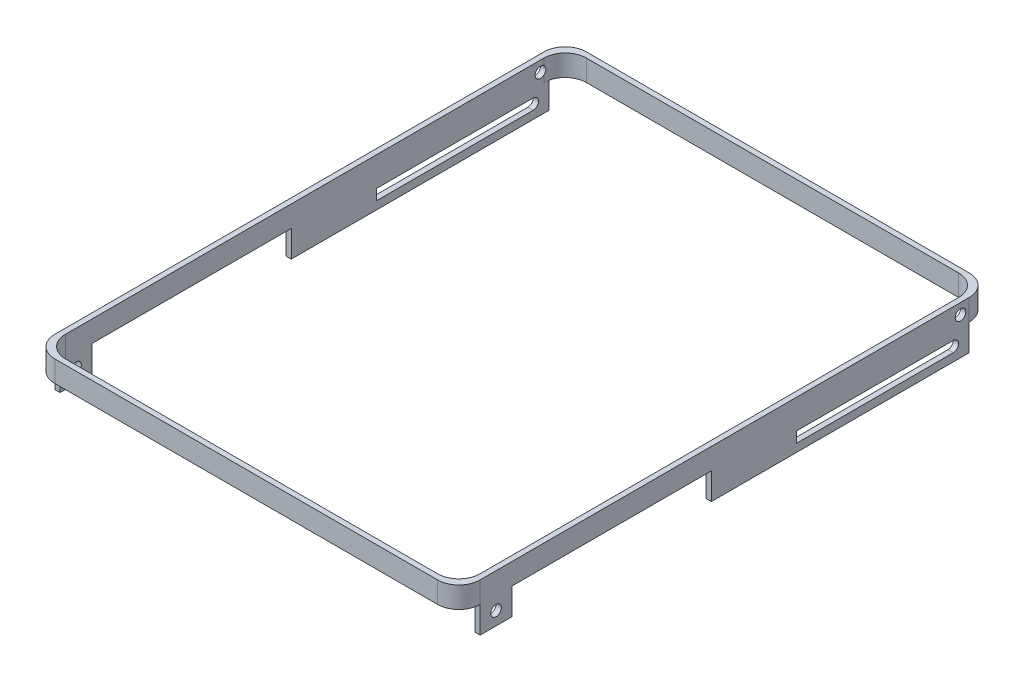
SolidWorks part; units mm, degrees
ref_plane "Front Plane" through (0, 0, 0) normal (0, 0, 1) x (1, 0, 0)
ref_plane "Top Plane" through (0, 0, 0) normal (0, 1, 0) x (1, 0, 0)
ref_plane "Right Plane" through (0, 0, 0) normal (1, 0, 0) x (0, 0, -1)
sketch "Sketch5" plane through (0, 0, 0) normal (0, 1, 0) x (1, 0, 0)
  line L1 (-180, 250) -> (180, 250)
  line L2 (-200, 230) -> (-200, -230)
  line L3 (-180, -250) -> (180, -250)
  line L4 (200, 230) -> (200, -230)
  line L5 (-200, 250) -> (200, -250) construction
  line L6 (-200, -250) -> (200, 250) construction
  arc A0 (-200, -230) -> (-180, -250) centre (-180, -230) ccw
  arc A1 (180, -250) -> (200, -230) centre (180, -230) ccw
  arc A2 (180, 250) -> (200, 230) centre (180, 230) cw
  arc A3 (-180, 250) -> (-200, 230) centre (-180, 230) ccw
  point P0 (0, 0)
  dimension "D3" = 20
  dimension "D1" = 500
  dimension "D2" = 400
extrude "Boss-Extrude2" add sketch "Sketch5" along normal blind 20
sketch "Sketch6" plane through (0, 20, 0) normal (0, 1, 0) x (1, 0, 0)
  line L1 (-175, -245) -> (175, -245)
  line L2 (-195, -225) -> (-195, 225)
  line L3 (-175, 245) -> (175, 245)
  line L4 (195, -225) -> (195, 225)
  line L5 (-195, -245) -> (195, 245) construction
  line L6 (-195, 245) -> (195, -245) construction
  arc A0 (-175, -245) -> (-195, -225) centre (-175, -225) cw
  arc A1 (175, -245) -> (195, -225) centre (175, -225) ccw
  arc A2 (175, 245) -> (195, 225) centre (175, 225) cw
  arc A3 (-195, 225) -> (-175, 245) centre (-175, 225) cw
  point P0 (0, 0)
  dimension "D3" = 20
  dimension "D1" = 490
  dimension "D2" = 390
extrude "Cut-Extrude1" cut sketch "Sketch6" against normal blind 20
sketch "Sketch7" plane through (200, 0, 0) normal (1, 0, 0) x (0, 0, -1)
  line L0 (230, 0) -> (230, -25)
  line L1 (230, -25) -> (-12.5565, -25)
  line L2 (-12.5565, -25) -> (-12.5565, 0)
  line L3 (-230, 0) -> (230, 0) construction
  line L4 (-12.5565, 0) -> (230, 0)
  dimension "D1" = 25
extrude "Boss-Extrude3" add sketch "Sketch7" against normal blind 5
sketch "Sketch8" plane through (-200, 0, 0) normal (-1, 0, 0) x (0, 0, 1)
  line L0 (-230, -25) -> (-230, 0) construction
  line L1 (12.5565, 0) -> (12.5565, -25) construction
  line L2 (12.5565, -25) -> (-230, -25) construction
  line L3 (-230, -25) -> (-230, 0)
  line L4 (12.5565, 0) -> (12.5565, -25)
  line L5 (12.5565, -25) -> (-230, -25)
  line L6 (-230, 0) -> (12.5565, 0)
extrude "Boss-Extrude4" add sketch "Sketch8" against normal blind 5
sketch "Sketch9" plane through (-200, 0, 0) normal (-1, 0, 0) x (0, 0, 1)
  line L0 (12.5565, 0) -> (-230, 0) construction
sketch "Sketch10" plane through (200, 0, 0) normal (1, 0, 0) x (0, 0, -1)
  line L10 (214.9751, -7.5) -> (2.4435, -7.5)
  line L13 (-12.5565, 0) -> (230, 0) construction
  line L15 (230, -25) -> (230, 0) construction
  line L16 (-12.5565, 0) -> (-12.5565, -25) construction
  line L18 (217.347, -16.9016) -> (215, -16.9016) construction
  line L20 (2.4435, -17.5) -> (214.9751, -17.5)
  arc A1 (2.4435, -7.5) -> (2.4435, -17.5) centre (2.4435, -12.5) ccw
  arc A3 (214.9751, -17.5) -> (214.9751, -7.5) centre (214.9751, -12.5) ccw
  dimension "D11" = 10
  dimension "D12" = 15.0249
  dimension "D14" = 5
  dimension "D13" = 15
  dimension "D15" = 212.5317
  dimension "D16" = 212.5317
extrude "Cut-Extrude2" cut sketch "Sketch10" against normal through all both and the other way through all
sketch "Sketch11" plane through (200, 0, 0) normal (1, 0, 0) x (0, 0, -1)
  line L0 (-230, 0) -> (-230, -25)
  line L1 (-230, -25) -> (-200, -25)
  line L2 (-200, -25) -> (-200, 0)
  line L3 (-230, 0) -> (-12.5565, 0) construction
  line L4 (-12.5565, -25) -> (-236.7643, -25) construction
  line L5 (-200, 0) -> (-230, 0)
  dimension "D1" = 30
  dimension "D2" = 25
extrude "Boss-Extrude5" add sketch "Sketch11" against normal blind 5
sketch "Sketch13" plane through (-200, 0, 0) normal (-1, 0, 0) x (0, 0, 1)
  line L0 (200, -25) -> (200, 0) construction
  line L1 (230, 0) -> (230, -25) construction
  line L2 (230, -25) -> (200, -25) construction
  line L3 (200, -25) -> (200, 0)
  line L4 (230, 0) -> (230, -25)
  line L5 (230, -25) -> (200, -25)
  line L6 (200, 0) -> (230, 0)
extrude "Boss-Extrude6" add sketch "Sketch13" against normal blind 5
sketch "Sketch14" plane through (-200, 0, 0) normal (-1, 0, 0) x (0, 0, 1)
  line L0 (-2.4435, -12.5) -> (215, -12.5) construction
  line L1 (230, -25) -> (230, 0) construction
  line L3 (12.5565, 0) -> (200, 0) construction
  line L5 (200, 0) -> (200, -25) construction
  line L6 (200, 0) -> (200, -25) construction
  circle A1 centre (215, -12.5) radius 5
  dimension "D2" = 10
  dimension "D1" = 15
extrude "Cut-Extrude3" cut sketch "Sketch14" against normal through all
sketch "Sketch16" plane through (-200, 0, 0) normal (-1, 0, 0) x (0, 0, 1)
  line L0 (-67.4435, -17.5) -> (-2.4435, -17.5)
  line L2 (-67.4435, -17.5) -> (-67.4435, -7.5)
  line L3 (-2.4435, -17.5) -> (-214.9751, -17.5) construction
  line L4 (-214.9751, -7.5) -> (-2.4435, -7.5) construction
  line L5 (-67.4435, -7.5) -> (-2.4435, -7.5)
  arc A0 (-2.4435, -17.5) -> (-2.4435, -7.5) centre (-2.4435, -12.5) ccw construction
  arc A1 (-2.4435, -17.5) -> (-2.4435, -7.5) centre (-2.4435, -12.5) ccw
extrude "Boss-Extrude7" add sketch "Sketch16" against normal blind 5
sketch "Sketch17" plane through (200, 0, 0) normal (1, 0, 0) x (0, 0, -1)
  line L0 (67.4435, -17.5) -> (67.4435, -7.5)
  line L1 (67.4435, -7.5) -> (2.4435, -7.5)
  line L2 (214.9751, -7.5) -> (2.4435, -7.5) construction
  line L3 (2.4435, -17.5) -> (67.4435, -17.5)
  line L4 (2.4435, -17.5) -> (214.9751, -17.5) construction
  arc A0 (2.4435, -7.5) -> (2.4435, -17.5) centre (2.4435, -12.5) ccw
extrude "Boss-Extrude8" add sketch "Sketch17" against normal blind 5
sketch "Sketch19" plane through (200, 0, 0) normal (1, 0, 0) x (0, 0, -1)
  circle A0 centre (221.7798, 10) radius 5
  dimension "D1" = 10
extrude "Cut-Extrude4" cut sketch "Sketch19" against normal through all
